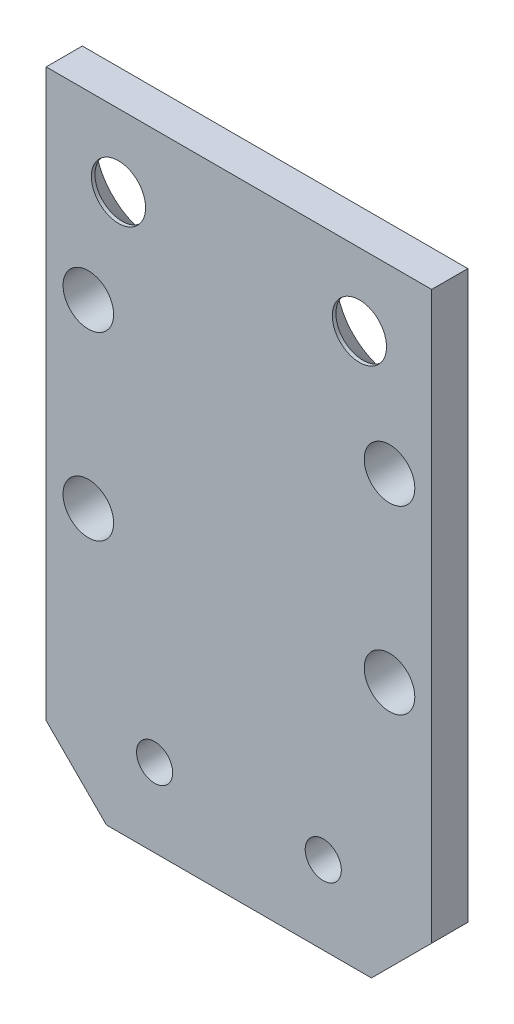
SolidWorks part; units mm, degrees
ref_plane "前视基准面" through (0, 0, 0) normal (0, 0, 1) x (1, 0, 0)
ref_plane "上视基准面" through (0, 0, 0) normal (0, 1, 0) x (1, 0, 0)
ref_plane "右视基准面" through (0, 0, 0) normal (1, 0, 0) x (0, 0, -1)
sketch "草图1" plane through (0, 0, 0) normal (0, 0, 1) x (1, 0, 0)
  line L0 (-16, -21) -> (-11, -26)
  line L1 (-11, -26) -> (11, -26)
  line L2 (-16, -21) -> (-16, 26)
  line L3 (-16, 26) -> (16, 26)
  line L4 (16, -21) -> (16, 26)
  line L5 (-16, -26) -> (16, 26) construction
  line L6 (-16, 26) -> (16, -26) construction
  line L7 (11, -26) -> (16, -21)
  line L8 (0, -26) -> (0, 26) construction
  circle A0 centre (-12.5, 11) radius 2.1
  circle A1 centre (12.5, 11) radius 2.1
  circle A2 centre (12.5, -4) radius 2.1
  circle A3 centre (-12.5, -4) radius 2.1
  circle A4 centre (-7, -19.5) radius 1.5
  circle A5 centre (7, -19.5) radius 1.5
  circle A6 centre (10, 20) radius 2.25
  circle A7 centre (-10, 20) radius 2.25
  point P0 (0, 0)
  dimension "D3" = 25
  dimension "D7" = 4.2
  dimension "D8" = 4.2
  dimension "D9" = 4.2
  dimension "D10" = 15
  dimension "D11" = 15
  dimension "D12" = 3
  dimension "D13" = 14
  dimension "D15" = 45.5
  dimension "D16" = 4.5
  dimension "D17" = 4.5
  dimension "D18" = 6
  dimension "D1" = 52
  dimension "D2" = 32
  dimension "D4" = 15
  dimension "D14" = 7
  dimension "D19" = 6
extrude "拉伸1" add sketch "草图1" along normal blind 3
chamfer "倒角2" distance 2.7 angle 45 1 edges at (12.25, 20, 0)
chamfer "倒角3" distance 2.7 angle 45 1 edges at (-7.75, 20, 0)
